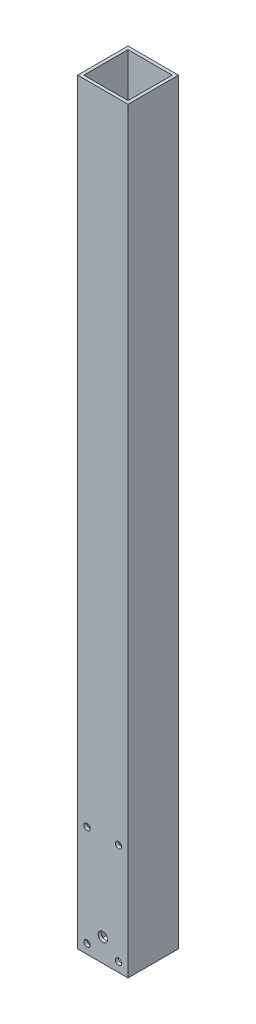
SolidWorks part; units mm, degrees
material "1060 Alloy"
ref_plane "Front Plane" through (0, 0, 0) normal (0, 0, 1) x (1, 0, 0)
ref_plane "Top Plane" through (0, 0, 0) normal (0, 1, 0) x (1, 0, 0)
ref_plane "Right Plane" through (0, 0, 0) normal (1, 0, 0) x (0, 0, -1)
sketch "Sketch1" plane through (0, 0, 0) normal (0, 1, 0) x (1, 0, 0)
  line L0 (3.175, 47.625) -> (47.625, 47.625)
  line L1 (0, 0) -> (50.8, 0)
  line L2 (0, 0) -> (0, 50.8)
  line L3 (0, 50.8) -> (50.8, 50.8)
  line L4 (50.8, 0) -> (50.8, 50.8)
  line L5 (47.625, 3.175) -> (47.625, 47.625)
  line L6 (3.175, 3.175) -> (47.625, 3.175)
  line L7 (3.175, 3.175) -> (3.175, 47.625)
  dimension "D1" = 50.8
  dimension "D2" = 3.175
extrude "Boss-Extrude1" add sketch "Sketch1" along normal blind 762
sketch "Sketch2" plane through (0, 0, 0) normal (0, 0, 1) x (1, 0, 0)
  line L0 (0, 762) -> (0, 0) construction
  line L1 (0, 0) -> (50.8, 0) construction
  line L2 (50.8, 762) -> (50.8, 0) construction
  circle A0 centre (9.525, 111.125) radius 3.175
  circle A1 centre (41.275, 111.125) radius 3.175
  circle A2 centre (9.525, 9.525) radius 3.175
  circle A3 centre (41.275, 9.525) radius 3.175
  circle A4 centre (25.4, 23.114) radius 4.7625
  point P13 (25.4, 0)
  dimension "D1" = 6.35
  dimension "D6" = 9.525
  dimension "D2" = 9.525
  dimension "D3" = 9.525
  dimension "D4" = 9.525
  dimension "D5" = 111.125
  dimension "D7" = 23.114
extrude "Cut-Extrude1" cut sketch "Sketch2" against normal through all
ref_plane "Plane1" [suppressed] through (0, 508, 0) normal (0, 1, 0) x (1, 0, 0)
mirror "Mirror1" [suppressed] about plane through (0, 508, 0) normal (0, 1, 0)
